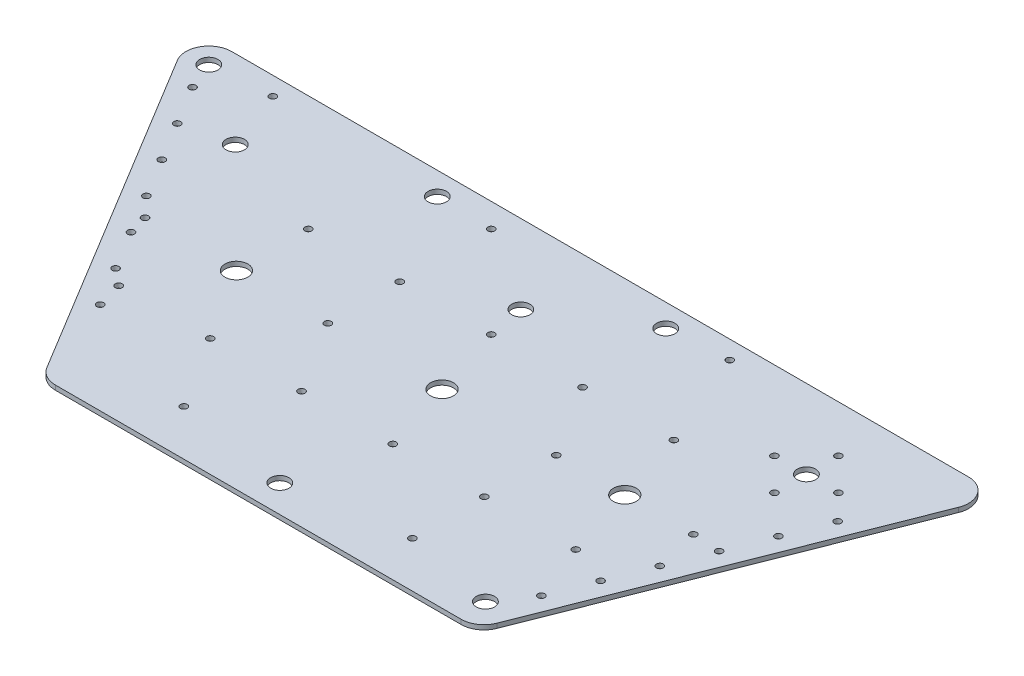
SolidWorks part; units mm, degrees
ref_plane "Front Plane" through (0, 0, 0) normal (0, 0, 1) x (1, 0, 0)
ref_plane "Top Plane" through (0, 0, 0) normal (0, 1, 0) x (1, 0, 0)
ref_plane "Right Plane" through (0, 0, 0) normal (1, 0, 0) x (0, 0, -1)
sketch "Sketch2" plane through (0, 0, 0) normal (0, 1, 0) x (1, 0, 0)
  line L0 (0, 0) -> (65, 165)
  line L1 (65, 165) -> (-290, 165)
  line L2 (-290, 165) -> (-190, 0)
  line L3 (-55, 0) -> (55, 0) construction
  line L4 (-190, 0) -> (0, 0)
  line L5 (0, -55) -> (0, 55) construction
  dimension "D1" = 355
  dimension "D2" = 190
  dimension "D3" = 165
  dimension "D4" = 65
extrude "Boss-Extrude1" add sketch "Sketch2" along normal blind 2
fillet "Fillet1" radius 10 4 edges at (-190, 1, 0) (-290, 1, -165) (65, 1, -165) (0, 1, 0)
sketch "Sketch3" plane through (0, 2, 0) normal (0, 1, 0) x (1, 0, 0)
  line L1 (50.3126, 165) -> (-272.2462, 165) construction
  line L2 (-280.7982, 149.817) -> (-192.9194, 4.817) construction
  line L3 (2.4955, 6.3348) -> (59.6167, 151.3348) construction
  line L5 (-1.1, 0) -> (1.1, 0) construction
  line L6 (-261.9073, 134.0821) -> (-194.8085, 23.369) construction
  line L7 (-4.3733, 10.7251) -> (45.6685, 137.7543) construction
  circle A0 centre (-272.2462, 155) radius 10 construction
  circle A1 centre (-228.1703, 83) radius 1.5
  circle A2 centre (-246.2462, 157) radius 1.5
  circle A3 centre (-46.2462, 157) radius 1.5
  circle A4 centre (11.8297, 83) radius 1.5
  circle A5 centre (13.8297, 130.5) radius 14 construction
  circle A6 centre (13.8297, 144.5) radius 1.5
  circle A7 centre (27.8297, 130.5) radius 1.5
  circle A8 centre (13.8297, 116.5) radius 1.5
  circle A9 centre (-0.1703, 130.5) radius 1.5
  circle A42 centre (-272.2462, 155) radius 4
  circle A43 centre (-172.2462, 155) radius 4
  circle A44 centre (13.8297, 130.5) radius 4
  circle A45 centre (-236.1703, 130.5) radius 4
  circle A46 centre (-111.1703, 130.5) radius 4
  circle A47 centre (-18.1703, 83) radius 5
  circle A48 centre (-188.1703, 83) radius 5
  circle A49 centre (-98.1703, 83) radius 5
  circle A50 centre (-205.05, 40.2675) radius 1.5
  circle A51 centre (-208.1703, 51.5) radius 1.5
  circle A52 centre (-225.7821, 74.4754) radius 1.5
  circle A53 centre (-236.1481, 91.5794) radius 1.5
  circle A54 centre (-246.5141, 108.6833) radius 1.5
  circle A55 centre (-256.8802, 125.7873) radius 1.5
  circle A56 centre (-267.2462, 142.8912) radius 1.5
  circle A57 centre (1.8297, 26.4713) radius 1.5
  circle A58 centre (9.1602, 45.0795) radius 1.5
  circle A59 centre (16.4907, 63.6876) radius 1.5
  circle A60 centre (23.8212, 82.2958) radius 1.5
  circle A61 centre (31.1517, 100.904) radius 1.5
  circle A62 centre (38.4822, 119.5121) radius 1.5
  circle A63 centre (-72.2462, 155) radius 4
  circle A64 centre (-148.1703, 154.5) radius 1.5
  circle A65 centre (-188.1703, 114.5) radius 1.5
  circle A66 centre (-148.1703, 114.5) radius 1.5
  circle A67 centre (-108.1703, 114.5) radius 1.5
  circle A68 centre (-68.1703, 114.5) radius 1.5
  circle A69 centre (-28.1703, 114.5) radius 1.5
  circle A70 centre (-148.1703, 83) radius 1.5
  circle A71 centre (-215.416, 57.3715) radius 1.5
  circle A72 centre (-168.1703, 51.5) radius 1.5
  circle A73 centre (-8.1703, 51.5) radius 1.5
  circle A74 centre (-128.1703, 51.5) radius 1.5
  circle A75 centre (-88.1703, 51.5) radius 1.5
  circle A76 centre (-48.1703, 83) radius 1.5
  circle A77 centre (-48.1703, 51.5) radius 1.5
  circle A78 centre (-8.1703, 12) radius 4
  circle A79 centre (-148.1703, 20) radius 1.5
  circle A80 centre (-98.1703, 12) radius 4
  circle A81 centre (-48.1703, 20) radius 1.5
  dimension "D1" = 3
  dimension "D2" = 8
  dimension "D3" = 20
  dimension "D4" = 20
  dimension "D6" = 20
  dimension "D7" = 20
  dimension "D8" = 20
  dimension "D9" = 8
  dimension "D10" = 5
  dimension "D11" = 20
  dimension "D12" = 12
  dimension "D13" = 31.5
  dimension "D14" = 31.5
  dimension "D15" = 31.5
  dimension "D16" = 40
  dimension "D17" = 40
  dimension "D18" = 40
  dimension "D19" = 40
  dimension "D20" = 40
  dimension "D21" = 40
  dimension "D22" = 12
  dimension "D24" = 40
  dimension "D25" = 90
  dimension "D26" = 80
  dimension "D27" = 50
  dimension "D28" = 10
  dimension "D29" = 40
  dimension "D30" = 40
  dimension "D31" = 40
  dimension "D32" = 40
  dimension "D33" = 3
  dimension "D34" = 16
  dimension "D35" = 125
  dimension "D37" = 8
  dimension "D38" = 10
  dimension "D39" = 20
  dimension "D40" = 20
  dimension "D41" = 20
  dimension "D42" = 20
  dimension "D43" = 20
  dimension "D44" = 100
  dimension "D45" = 100
  dimension "D46" = 40
  dimension "D47" = 30
  dimension "D48" = 8
  dimension "D5" = 20
  dimension "D23" = 90
  dimension "D36" = 125
  dimension "D49" = 26
  dimension "D50" = 200
  dimension "D51" = 3
  dimension "D52" = 28
extrude "Cut-Extrude1" cut sketch "Sketch3" against normal blind 2
